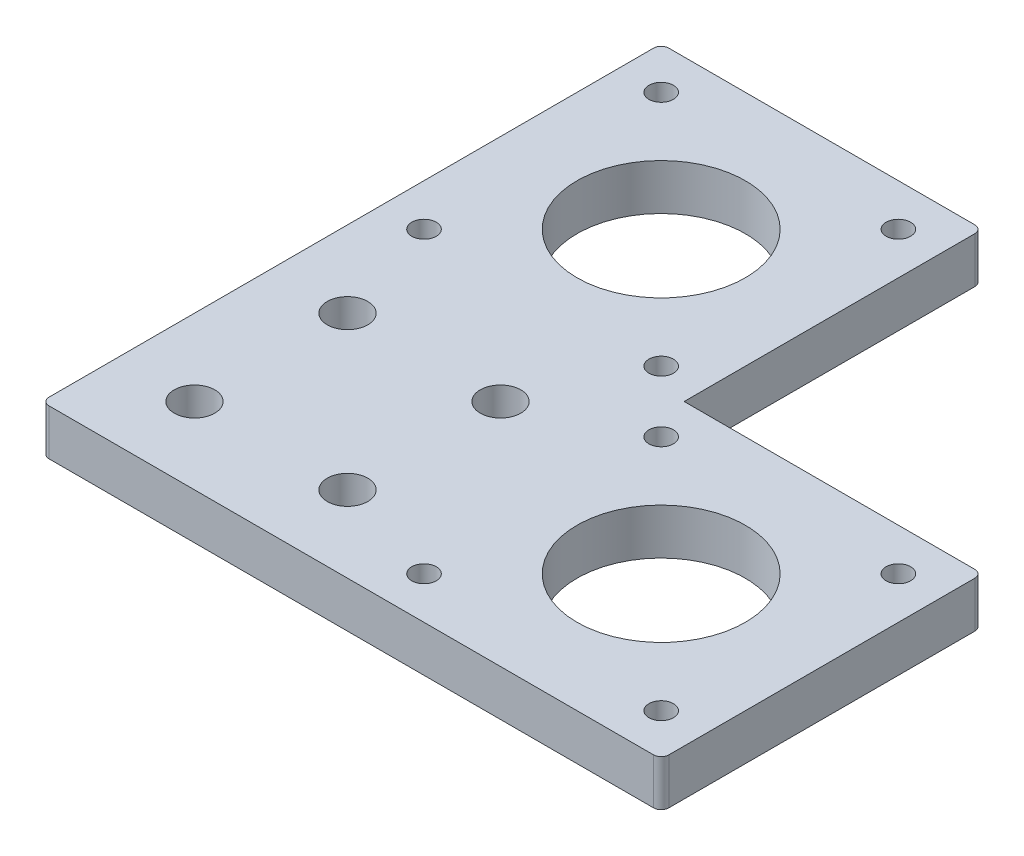
SolidWorks part; units mm, degrees
material "ASTM A36 Steel"
ref_plane "Front Plane" through (0, 0, 0) normal (0, 0, 1) x (1, 0, 0)
ref_plane "Top Plane" through (0, 0, 0) normal (0, 1, 0) x (1, 0, 0)
ref_plane "Right Plane" through (0, 0, 0) normal (1, 0, 0) x (0, 0, -1)
sketch "Sketch1" plane through (0, 0, 0) normal (0, 1, 0) x (1, 0, 0)
  line L0 (0, 0) -> (81, 0)
  line L1 (81, 0) -> (81, 42)
  line L2 (81, 42) -> (42, 42)
  line L3 (42, 42) -> (42, 81)
  line L4 (42, 81) -> (0, 81)
  line L5 (0, 81) -> (0, 0)
  line L7 (30, 10) -> (10, 10) construction
  line L8 (30, 10) -> (30, 30) construction
  line L9 (30, 30) -> (10, 30) construction
  line L10 (10, 10) -> (10, 30) construction
  line L11 (30, 10) -> (10, 30) construction
  line L12 (30, 30) -> (10, 10) construction
  line L13 (75.5, 5.5) -> (44.5, 5.5) construction
  line L14 (75.5, 5.5) -> (75.5, 36.5) construction
  line L15 (75.5, 36.5) -> (44.5, 36.5) construction
  line L16 (44.5, 5.5) -> (44.5, 36.5) construction
  line L17 (75.5, 5.5) -> (44.5, 36.5) construction
  line L18 (75.5, 36.5) -> (44.5, 5.5) construction
  line L19 (5.5, 44.5) -> (36.5, 44.5) construction
  line L20 (5.5, 44.5) -> (5.5, 75.5) construction
  line L21 (5.5, 75.5) -> (36.5, 75.5) construction
  line L22 (36.5, 44.5) -> (36.5, 75.5) construction
  line L23 (5.5, 44.5) -> (36.5, 75.5) construction
  line L24 (5.5, 75.5) -> (36.5, 44.5) construction
  point P3 (20, 20)
  point P12 (21, 60)
  point P13 (60, 21)
  point P14 (21, 60)
  point P15 (81, 21)
  point P17 (21, 81)
  point P18 (60, 21)
  dimension "D1" = 20
  dimension "D2" = 10
  dimension "D3" = 10
  dimension "D4" = 42
  dimension "D5" = 60
  dimension "D6" = 60
  dimension "D7" = 31
  dimension "D8" = 5.5
  dimension "D9" = 5.5
extrude "Boss-Extrude1" add sketch "Sketch1" along normal blind 6
hole_wizard "M5 Clearance Hole1" positions "Sketch2" profile "Sketch3" hole size "M5" standard "ANSI Metric" end condition through all
sketch "Sketch2" plane through (0, 6, 0) normal (0, 1, 0) x (1, 0, 0)
  point P0 (10, 30)
  point P3 (30, 30)
  point P6 (30, 10)
  point P9 (10, 10)
sketch "Sketch3" plane through (10, 6, -30) normal (1, 0, 0) x (0, 0, 1)
  line L0 (0, 0) -> (0, 6)
  line L1 (0, 6) -> (2.65, 6)
  line L2 (2.65, 6) -> (2.65, 0)
  line L5 (2.65, 0) -> (0, 0)
  line L11 (0, -6.35) -> (0, 107.95) construction
  dimension "Thru Hole Dia." = 5.3
  dimension "Thru Hole Depth" = 6
hole_wizard "M3 Clearance Hole1" positions "Sketch4" profile "Sketch5" hole size "M3" standard "ANSI Metric" end condition through all
sketch "Sketch4" plane through (0, 6, 0) normal (0, 1, 0) x (1, 0, 0)
  point P0 (5.5, 44.5)
  point P3 (36.5, 44.5)
  point P6 (36.5, 75.5)
  point P9 (5.5, 75.5)
  point P12 (44.5, 36.5)
  point P15 (44.5, 5.5)
  point P18 (75.5, 5.5)
  point P21 (75.5, 36.5)
sketch "Sketch5" plane through (5.5, 6, -44.5) normal (1, 0, 0) x (0, 0, 1)
  line L0 (0, 0) -> (0, 6)
  line L1 (0, 6) -> (1.6, 6)
  line L2 (1.6, 6) -> (1.6, 0)
  line L5 (1.6, 0) -> (0, 0)
  line L11 (0, -6.35) -> (0, 107.95) construction
  dimension "Thru Hole Dia." = 3.2
  dimension "Thru Hole Depth" = 6
hole_wizard "Ø22.0 (22) Diameter Hole1" positions "Sketch6" profile "Sketch7" hole size "Ø22.0" standard "ANSI Metric" end condition through all
sketch "Sketch6" plane through (0, 6, 0) normal (0, 1, 0) x (1, 0, 0)
  point P0 (60, 21)
  point P3 (21, 60)
sketch "Sketch7" plane through (60, 6, -21) normal (1, 0, 0) x (0, 0, 1)
  line L0 (0, 0) -> (0, 6)
  line L1 (0, 6) -> (11, 6)
  line L2 (11, 6) -> (11, 0)
  line L5 (11, 0) -> (0, 0)
  line L11 (0, -6.35) -> (0, 107.95) construction
  dimension "Thru Hole Dia." = 22
  dimension "Thru Hole Depth" = 6
fillet "Fillet1" radius 1 5 edges at (0, 3, -81) (42, 3, -81) (81, 3, -42) (81, 3, 0) (0, 3, 0)
